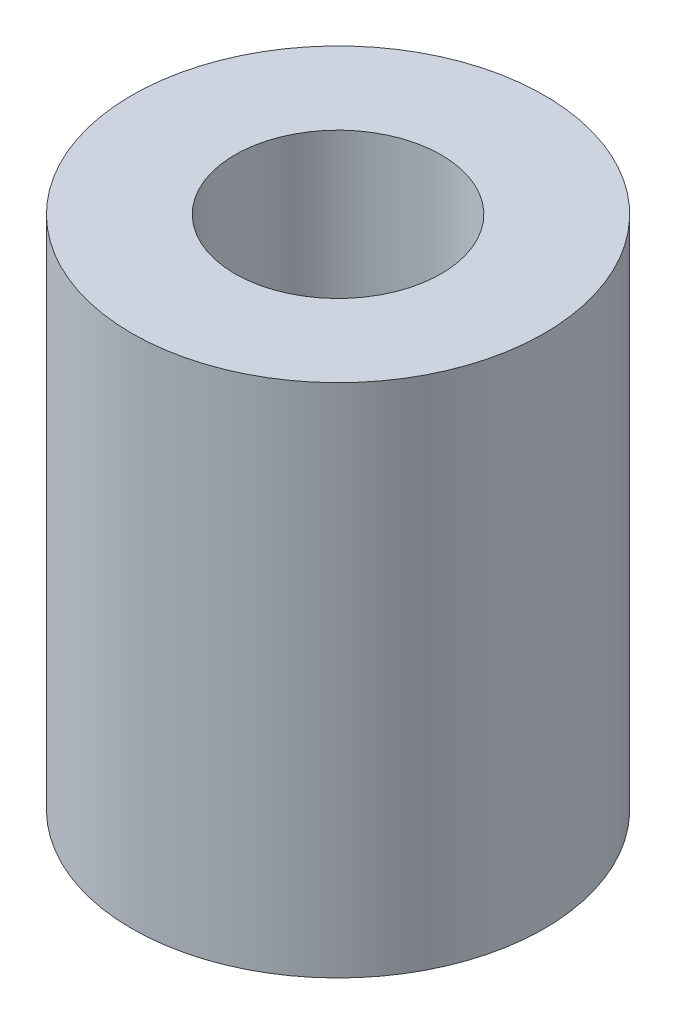
SolidWorks part; units mm, degrees
ref_plane "正面" through (0, 0, 0) normal (0, 0, 1) x (1, 0, 0)
ref_plane "平面" through (0, 0, 0) normal (0, 1, 0) x (1, 0, 0)
ref_plane "右側面" through (0, 0, 0) normal (1, 0, 0) x (0, 0, -1)
sketch "ｽｹｯﾁ1" plane through (0, 0, 0) normal (0, 1, 0) x (1, 0, 0)
  circle A0 centre (0, 0) radius 10
  circle A1 centre (0, 0) radius 5
  dimension "D1" = 20
  dimension "D2" = 10
extrude "ﾎﾞｽ - 押し出し1" add sketch "ｽｹｯﾁ1" along normal mid plane 25
